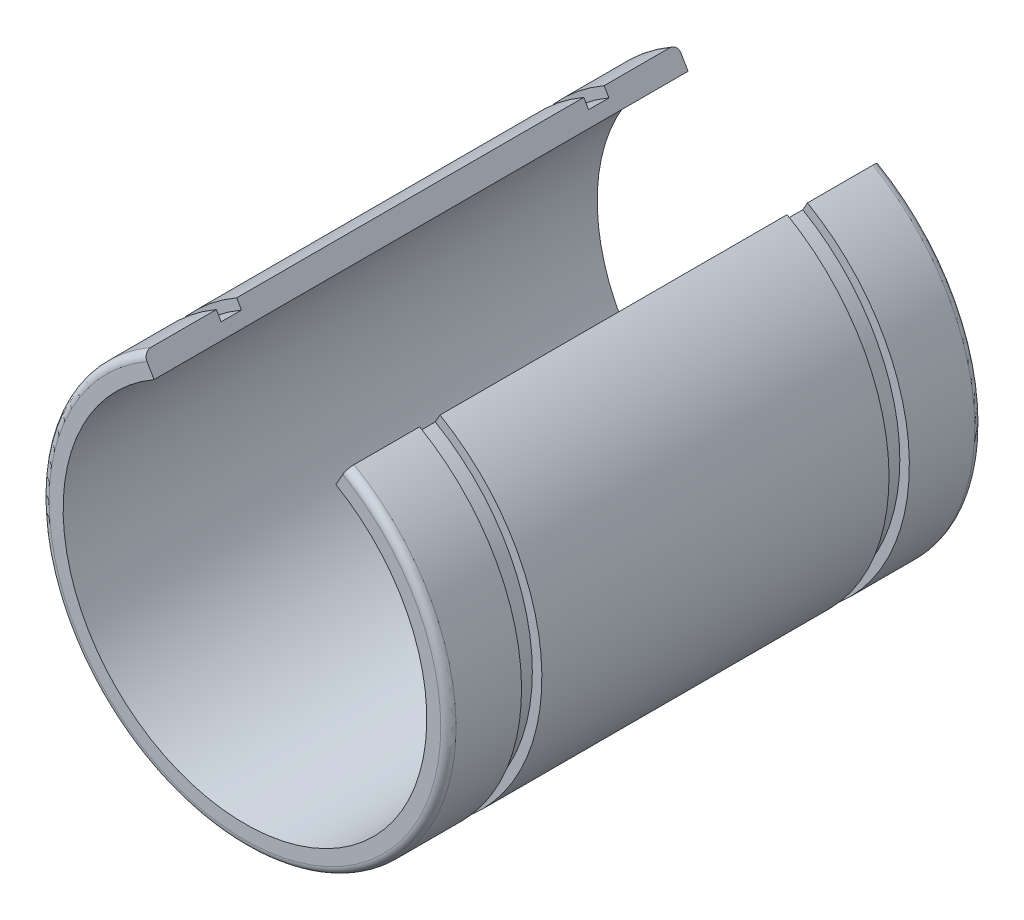
SolidWorks part; units mm, degrees
ref_plane "Front Plane" through (0, 0, 0) normal (0, 0, 1) x (1, 0, 0)
ref_plane "Top Plane" through (0, 0, 0) normal (0, 1, 0) x (1, 0, 0)
ref_plane "Right Plane" through (0, 0, 0) normal (1, 0, 0) x (0, 0, -1)
sketch "Sketch1" plane through (0, 0, 0) normal (0, 0, 1) x (1, 0, 0)
  line L0 (0, 16) -> (0, -16) construction
  line L1 (0, 0) -> (8, 13.8564) construction
  line L2 (0, 0) -> (-8, 13.8564) construction
  line L3 (-8, 13.8564) -> (-7.15, 12.3842)
  line L4 (7.9865, 13.8642) -> (7.15, 12.3842)
  circle A0 centre (0, 0) radius 16 construction
  circle A1 centre (0, 0) radius 14.3 construction
  arc A2 (-8, 13.8564) -> (7.9865, 13.8642) centre (0, 0) ccw
  arc A3 (-7.15, 12.3842) -> (7.15, 12.3842) centre (0, 0) ccw
  dimension "D1" = 32
  dimension "D2" = 28.6
  dimension "D3" = 60
  dimension "D4" = 30
extrude "Boss-Extrude1" add sketch "Sketch1" along normal blind 42
sketch "Sketch2" plane through (0, 0, 0) normal (0, 1, 0) x (1, 0, 0)
  line L0 (0, 0) -> (0, -42) construction
  line L1 (-14.3, -42) -> (14.3, -42) construction
  line L2 (0, 0) -> (16, 0) construction
  line L3 (16, 0) -> (16, -42) construction
  line L4 (16, -42) -> (0, -42) construction
  line L5 (-16, -21) -> (16, -21) construction
  line L6 (16, -36.25) -> (15.25, -36.25)
  line L7 (16, -36.25) -> (16, -34.65)
  line L8 (16, -34.65) -> (15.25, -34.65)
  line L9 (15.25, -36.25) -> (15.25, -34.65)
  line L10 (-16, 0) -> (-16, -42) construction
  line L11 (16, -5.75) -> (15.25, -5.75)
  line L12 (16, -7.35) -> (15.25, -7.35)
  line L13 (16, -5.75) -> (16, -7.35)
  line L14 (15.25, -5.75) -> (15.25, -7.35)
  dimension "D1" = 1.6
  dimension "D2" = 0.75
  dimension "D3" = 30.5
revolve "Cut-Revolve1" cut sketch "Sketch2" angle 360 about L0
fillet "Fillet1" radius 0.6 2 edges at (0.0078, -16, 0) (0.0078, -16, 42)
